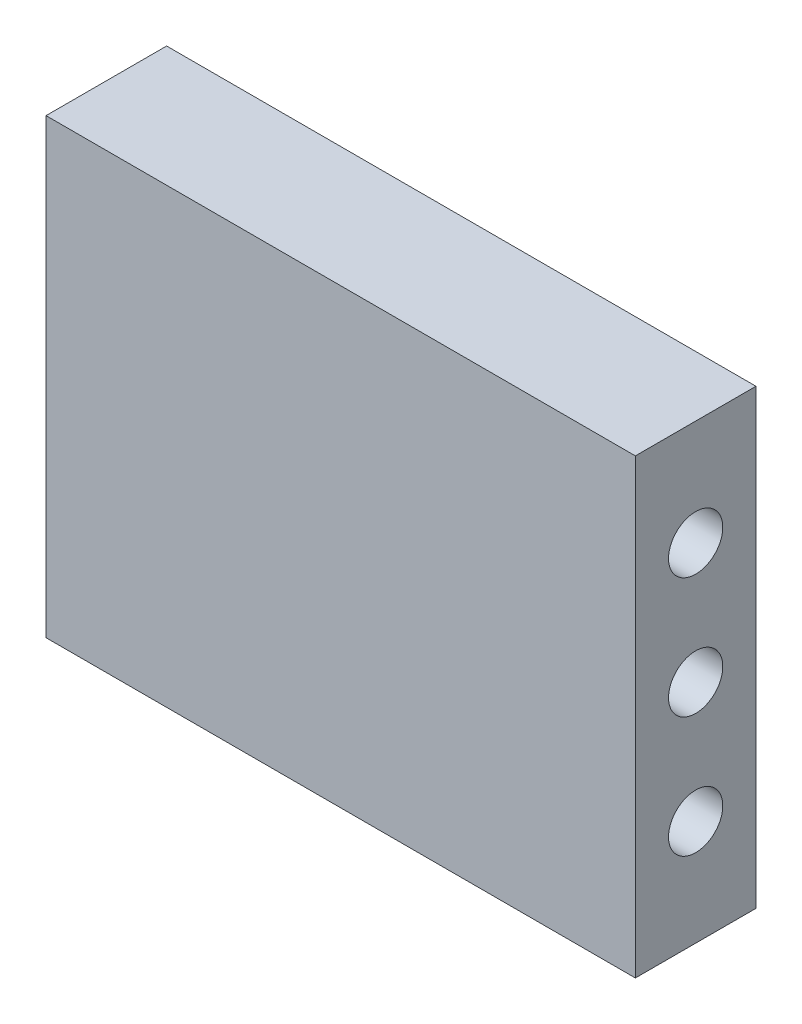
SolidWorks part; units mm, degrees
material "ABS"
ref_plane "前基準面" through (0, 0, 0) normal (0, 0, 1) x (1, 0, 0)
ref_plane "上基準面" through (0, 0, 0) normal (0, 1, 0) x (1, 0, 0)
ref_plane "右基準面" through (0, 0, 0) normal (1, 0, 0) x (0, 0, -1)
sketch "草圖1" plane through (0, 0, 0) normal (0, 0, 1) x (1, 0, 0)
  line L1 (-3.7025, 11.8902) -> (35.3975, 11.8902)
  line L2 (-3.7025, 11.8902) -> (-3.7025, -18.1098)
  line L3 (-3.7025, -18.1098) -> (35.3975, -18.1098)
  line L4 (35.3975, 11.8902) -> (35.3975, -18.1098)
  dimension "D1" = 30
  dimension "D2" = 39.1
extrude "填料-伸長1" add sketch "草圖1" along normal blind 8
sketch "草圖2" plane through (-3.7025, 0, 0) normal (-1, 0, 0) x (0, 0, 1)
  line L0 (8, 11.8902) -> (0, 11.8902) construction
  line L1 (8, 11.8902) -> (8, -18.1098) construction
  circle A0 centre (4, 4.8902) radius 1.8
  circle A1 centre (4, -3.1098) radius 1.8
  circle A2 centre (4, -11.1098) radius 1.8
  dimension "D1" = 3.6
  dimension "D2" = 7
  dimension "D3" = 4
  dimension "D4" = 3
extrude "除料-伸長1" cut sketch "草圖2" against normal through all
